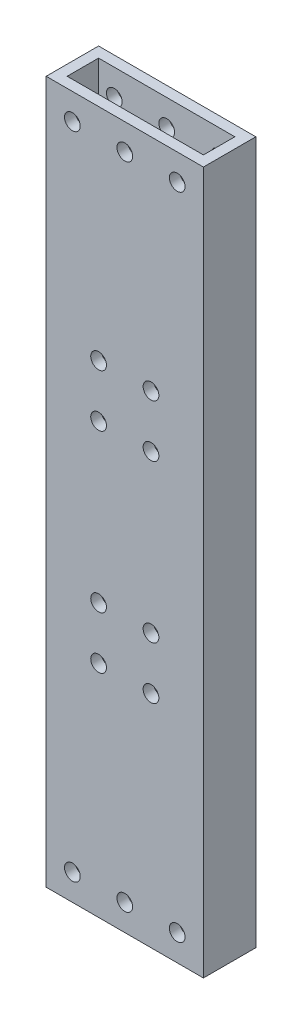
SolidWorks part; units mm, degrees
ref_plane "前视基准面" through (0, 0, 0) normal (0, 0, 1) x (1, 0, 0)
ref_plane "上视基准面" through (0, 0, 0) normal (0, 1, 0) x (1, 0, 0)
ref_plane "右视基准面" through (0, 0, 0) normal (1, 0, 0) x (0, 0, -1)
sketch "草图1" plane through (0, 0, 0) normal (0, 1, 0) x (1, 0, 0)
  line L1 (-15, 5) -> (15, 5)
  line L2 (-15, 5) -> (-15, -5)
  line L3 (-15, -5) -> (15, -5)
  line L4 (15, 5) -> (15, -5)
  line L5 (-15, 5) -> (15, -5) construction
  line L6 (-15, -5) -> (15, 5) construction
  line L7 (-13, 3) -> (13, 3)
  line L8 (-13, 3) -> (-13, -3)
  line L9 (-13, -3) -> (13, -3)
  line L10 (13, 3) -> (13, -3)
  line L11 (-13, 3) -> (13, -3) construction
  line L12 (-13, -3) -> (13, 3) construction
  point P0 (0, 0)
  point P6 (0, 0)
  dimension "D1" = 30
  dimension "D2" = 10
  dimension "D3" = 2
  dimension "D4" = 2
extrude "凸台-拉伸1" add sketch "草图1" along normal mid plane 134
sketch "草图2" plane through (0, 0, 5) normal (0, 0, 1) x (1, 0, 0)
  line L0 (10, 62) -> (-10, 62) construction
  line L1 (15, 67) -> (15, -67) construction
  line L2 (-15, 67) -> (15, 67) construction
  line L3 (0, 0) -> (35.5683, 0) construction
  line L4 (-15, 67) -> (-15, -67) construction
  line L5 (-5, 25) -> (5, 25) construction
  line L6 (-5, 25) -> (-5, 15) construction
  line L7 (-5, 15) -> (5, 15) construction
  line L8 (5, 25) -> (5, 15) construction
  line L9 (-5, 25) -> (5, 15) construction
  line L10 (-5, 15) -> (5, 25) construction
  line L11 (-160, 30) -> (160, 30) construction
  line L12 (-160, 10) -> (160, 10) construction
  circle A0 centre (-10, 62) radius 1.5
  circle A1 centre (0, 62) radius 1.5
  circle A2 centre (10, 62) radius 1.5
  circle A3 centre (0, 72) radius 1.5 construction
  circle A4 centre (-5, 25) radius 1.5
  circle A5 centre (-5, 15) radius 1.5
  circle A6 centre (5, 15) radius 1.5
  circle A7 centre (5, 25) radius 1.5
  circle A8 centre (-5, -15) radius 1.5
  circle A9 centre (5, -15) radius 1.5
  circle A10 centre (5, -25) radius 1.5
  circle A11 centre (-5, -25) radius 1.5
  circle A12 centre (-10, -62) radius 1.5
  circle A13 centre (0, -62) radius 1.5
  circle A14 centre (10, -62) radius 1.5
  point P14 (0, 20)
  dimension "D1" = 5
  dimension "D2" = 10
  dimension "D3" = 10
  dimension "D4" = 5
  dimension "D5" = 10
  dimension "D6" = 10
  dimension "D7" = 5
  dimension "D8" = 5
extrude "切除-拉伸1" cut sketch "草图2" against normal through all
